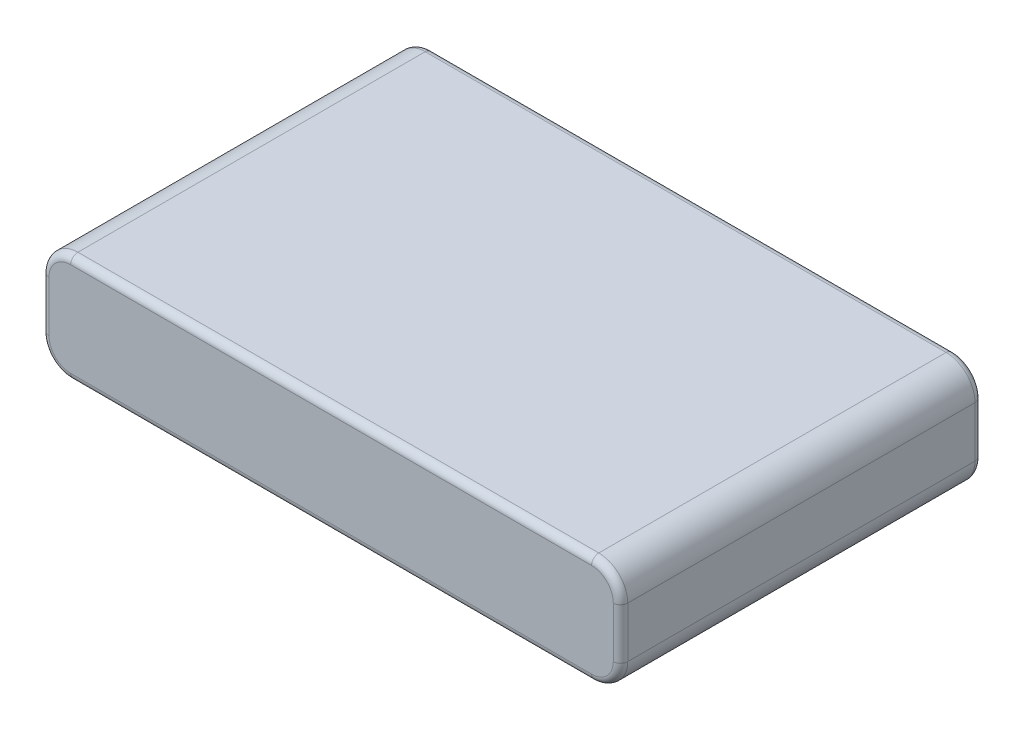
SolidWorks part; units mm, degrees
ref_plane "Ön Düzlem" through (0, 0, 0) normal (0, 0, 1) x (1, 0, 0)
ref_plane "Üst Düzlem" through (0, 0, 0) normal (0, 1, 0) x (1, 0, 0)
ref_plane "Sağ Düzlem" through (0, 0, 0) normal (1, 0, 0) x (0, 0, -1)
sketch "Sketch1" plane through (0, 0, 0) normal (0, 1, 0) x (1, 0, 0)
  line L1 (0, 0) -> (40, 0)
  line L2 (0, 0) -> (0, 25)
  line L3 (0, 25) -> (40, 25)
  line L4 (40, 0) -> (40, 25)
  dimension "D1" = 25
  dimension "D2" = 40
extrude "Boss-Extrude1" add sketch "Sketch1" along normal blind 7.5
fillet "Fillet2" radius 2 1 edges at (40, 7.5, -12.5)
fillet "Fillet3" radius 2 1 edges at (40, 0, -12.5)
fillet "Fillet4" radius 2 2 edges at (0, 0, -12.5) (0, 7.5, -12.5)
fillet "Fillet5" radius 0.5 8 edges at (0.5858, 6.9142, 0) (0, 3.75, 0) (0.5858, 0.5858, 0) (20, 0, 0) (39.4142, 0.5858, 0) (40, 3.75, 0) (39.4142, 6.9142, 0) (20, 7.5, 0)
fillet "Fillet6" radius 0.5 8 edges at (39.4142, 6.9142, -25) (40, 3.75, -25) (39.4142, 0.5858, -25) (20, 0, -25) (0.5858, 0.5858, -25) (0, 3.75, -25) (0.5858, 6.9142, -25) (20, 7.5, -25)
